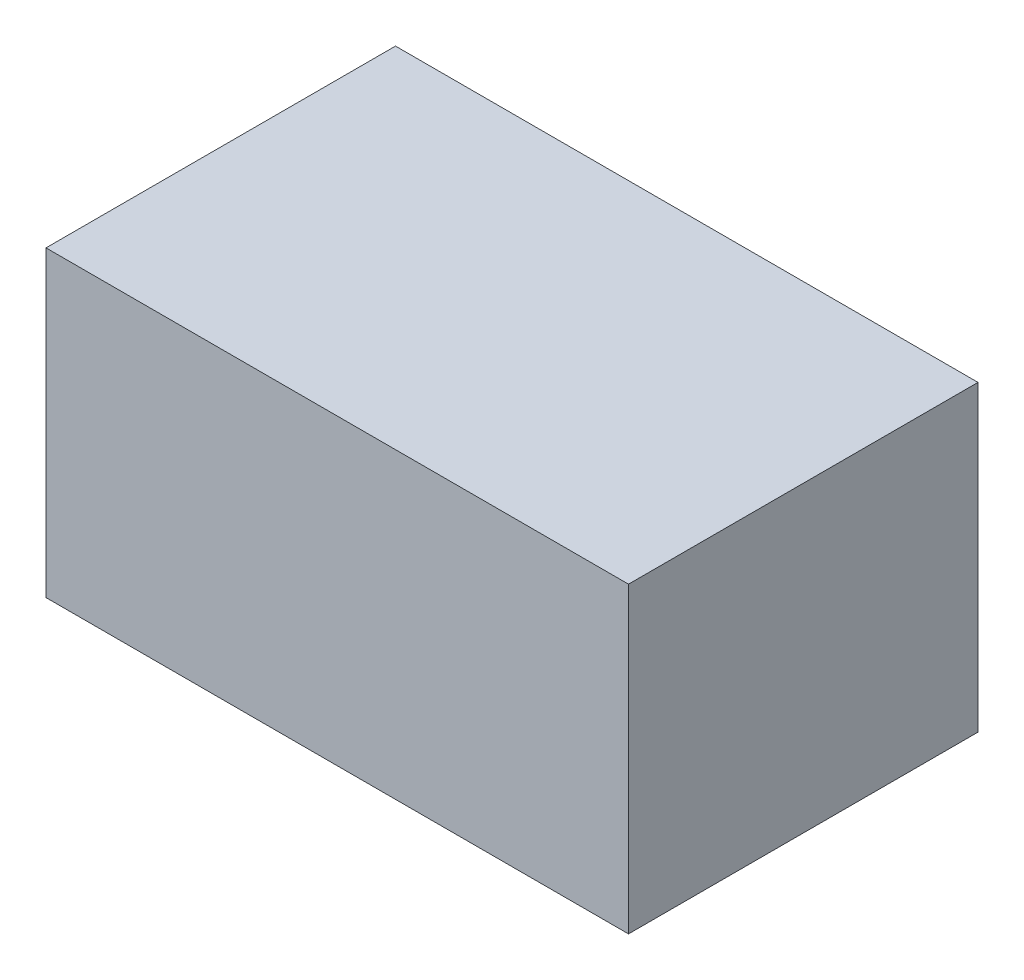
SolidWorks part; units mm, degrees
ref_plane "Alzado" through (0, 0, 0) normal (0, 0, 1) x (1, 0, 0)
ref_plane "Planta" through (0, 0, 0) normal (0, 1, 0) x (1, 0, 0)
ref_plane "Vista lateral" through (0, 0, 0) normal (1, 0, 0) x (0, 0, -1)
sketch "Croquis1" plane through (0, 0, 0) normal (0, 1, 0) x (1, 0, 0)
  line L1 (-125, -75) -> (125, -75)
  line L2 (-125, -75) -> (-125, 75)
  line L3 (-125, 75) -> (125, 75)
  line L4 (125, -75) -> (125, 75)
  line L5 (-125, -75) -> (125, 75) construction
  line L6 (-125, 75) -> (125, -75) construction
  point P0 (0, 0)
  dimension "D1" = 250
  dimension "D2" = 150
extrude "Saliente-Extruir1" add sketch "Croquis1" along normal blind 130
